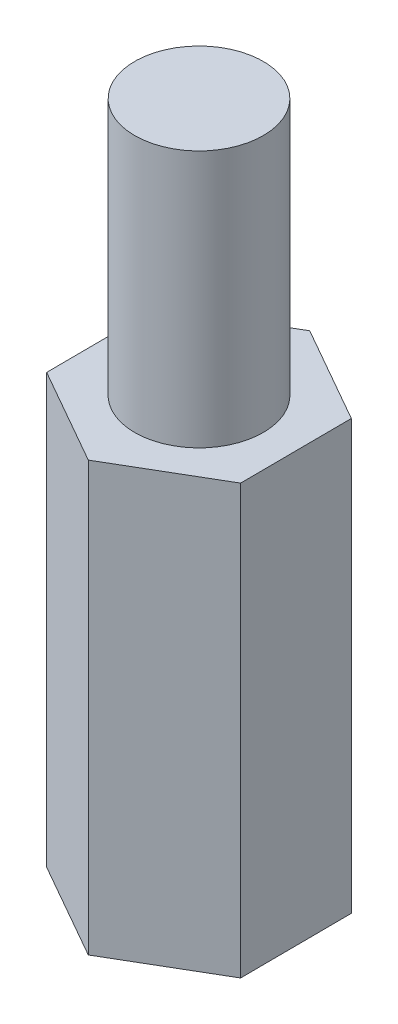
SolidWorks part; units mm, degrees
ref_plane "Front Plane" through (0, 0, 0) normal (0, 0, 1) x (1, 0, 0)
ref_plane "Top Plane" through (0, 0, 0) normal (0, 1, 0) x (1, 0, 0)
ref_plane "Right Plane" through (0, 0, 0) normal (1, 0, 0) x (0, 0, -1)
sketch "Sketch1" plane through (0, 0, 0) normal (0, 1, 0) x (1, 0, 0)
  line L1 (2.2574, -1.2862) -> (2.2426, 1.3119)
  line L2 (2.2426, 1.3119) -> (-0.0148, 2.598)
  line L3 (-0.0148, 2.598) -> (-2.2574, 1.2862)
  line L4 (-2.2574, 1.2862) -> (-2.2426, -1.3119)
  line L5 (-2.2426, -1.3119) -> (0.0148, -2.598)
  line L6 (0.0148, -2.598) -> (2.2574, -1.2862)
  circle A0 centre (0, 0) radius 2.25 construction
  dimension "D1" = 4.5
extrude "Boss-Extrude1" add sketch "Sketch1" along normal blind 10
sketch "Sketch2" plane through (0, 10, 0) normal (0, 1, 0) x (1, 0, 0)
  circle A0 centre (0, 0) radius 1.5
  dimension "D1" = 3
extrude "Boss-Extrude2" add sketch "Sketch2" along normal blind 6
